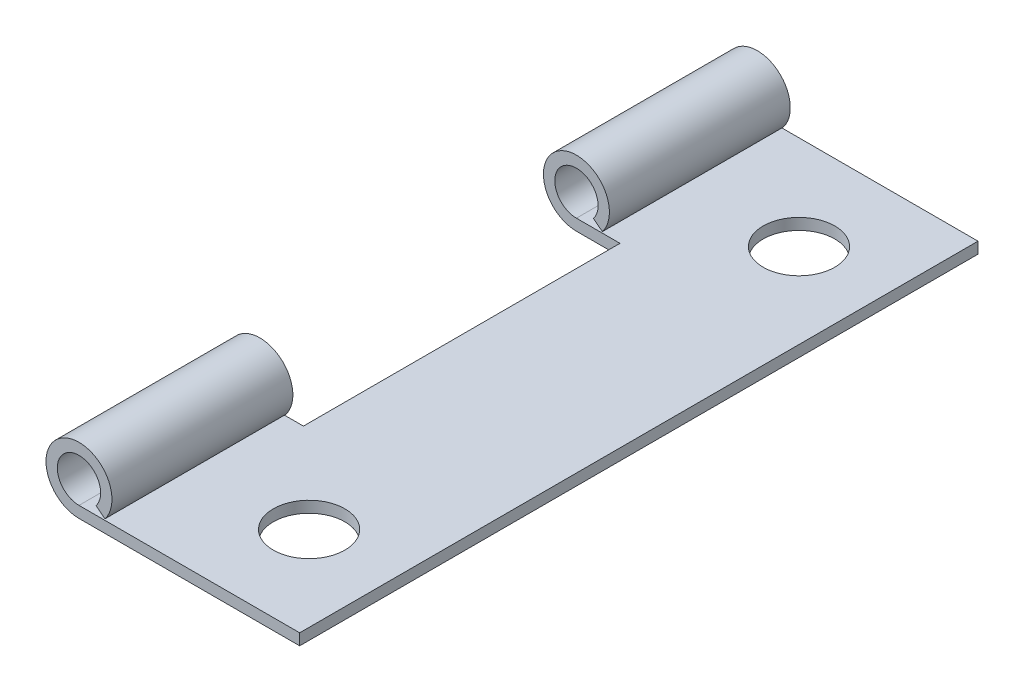
SolidWorks part; units mm, degrees
material "Latón"
ref_plane "Front" through (0, 0, 0) normal (0, 0, 1) x (1, 0, 0)
ref_plane "Top" through (0, 0, 0) normal (0, 1, 0) x (1, 0, 0)
ref_plane "Right" through (0, 0, 0) normal (1, 0, 0) x (0, 0, -1)
sketch "Sketch1" plane through (0, 0, 0) normal (0, 0, 1) x (1, 0, 0)
  line L0 (0, 0) -> (-13.4621, 0) construction
  line L1 (-13.4621, 0) -> (-13.4621, 5) construction
  line L2 (0, 0) -> (0, 0.6)
  line L3 (0, 0.6) -> (-11.7121, 0.6)
  line L4 (-11.7121, 0) -> (0, 0)
  line L5 (-10.8073, 1.0402) -> (-10.3352, 0.6699)
  circle A0 centre (-11.7121, 1.75) radius 1.75 construction
  arc A1 (-11.7121, 0) -> (-10.3352, 0.6699) centre (-11.7121, 1.75) cw
  circle A2 centre (-11.7121, 1.75) radius 1.15 construction
  arc A3 (-11.7121, 0.6) -> (-10.8073, 1.0402) centre (-11.7121, 1.75) cw
  dimension "D1" = 3.5
  dimension "D3" = 2.3
  dimension "D2" = 5
extrude "Boss-Extrude1" add sketch "Sketch1" along normal blind 36
sketch "Sketch2" plane through (0, 0.6, 0) normal (0, 1, 0) x (1, 0, 0)
  line L0 (-4.5, 0) -> (-4.5, -36) construction
  line L1 (0, 0) -> (-11.7121, 0) construction
  line L2 (0, -36) -> (-11.7121, -36) construction
  line L3 (0, -36) -> (0, 0) construction
  line L4 (0, -18) -> (-13.4621, -18) construction
  line L5 (-13.4621, 0) -> (-13.4621, -36) construction
  circle A0 centre (-4.5, -5) radius 1.9
  circle A1 centre (-4.5, -31) radius 1.9
  dimension "D2" = 3.8
  dimension "D1" = 4.5
  dimension "D3" = 5
extrude "Cut-Extrude1" cut sketch "Sketch2" against normal through all
sketch "Sketch3" plane through (0, 0.6, 0) normal (0, 1, 0) x (1, 0, 0)
  line L0 (-13.4621, 0) -> (-13.4621, -36) construction
  line L1 (-17.5243, -9.6) -> (-9.4, -9.6)
  line L2 (-17.5243, -9.6) -> (-17.5243, -26.4)
  line L3 (-17.5243, -26.4) -> (-9.4, -26.4)
  line L4 (-9.4, -9.6) -> (-9.4, -26.4)
  line L5 (-17.5243, -9.6) -> (-9.4, -26.4) construction
  line L6 (-17.5243, -26.4) -> (-9.4, -9.6) construction
  line L7 (0, -36) -> (0, 0) construction
  point P0 (-13.4621, -18)
  dimension "D1" = 16.8
  dimension "D2" = 9.4
extrude "Cut-Extrude2" cut sketch "Sketch3" against normal through all both and the other way through all
